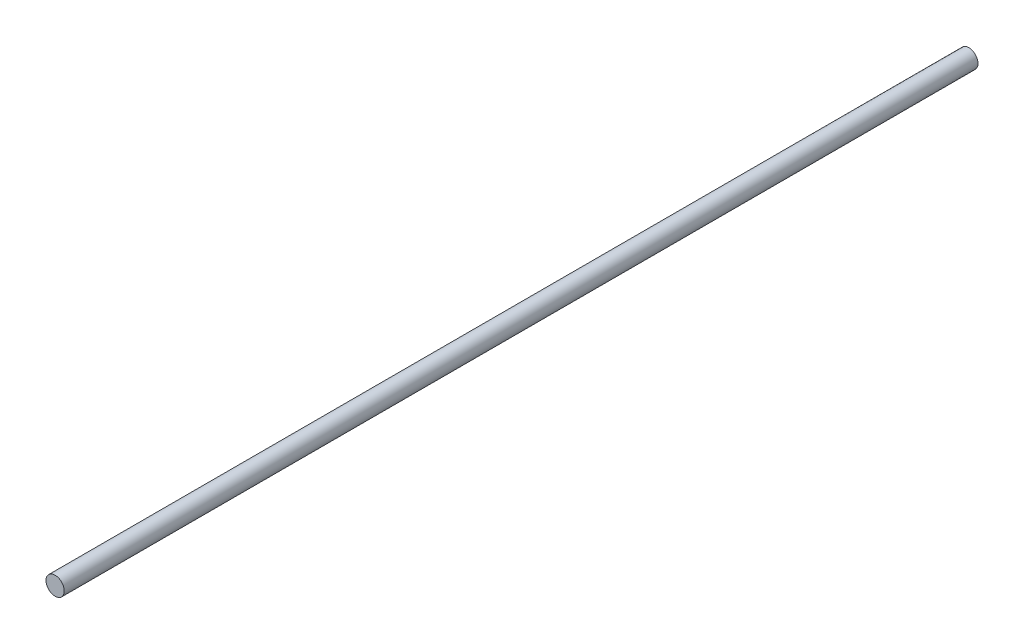
SolidWorks part; units mm, degrees
ref_plane "Front Plane" through (0, 0, 0) normal (0, 0, 1) x (1, 0, 0)
ref_plane "Top Plane" through (0, 0, 0) normal (0, 1, 0) x (1, 0, 0)
ref_plane "Right Plane" through (0, 0, 0) normal (1, 0, 0) x (0, 0, -1)
sketch "Sketch1" plane through (0, 0, 0) normal (0, 0, 1) x (1, 0, 0)
  circle A0 centre (0, 0) radius 4
  point P3 (14.7021, 22.7581)
extrude "Boss-Extrude1" add sketch "Sketch1" along normal blind 400
